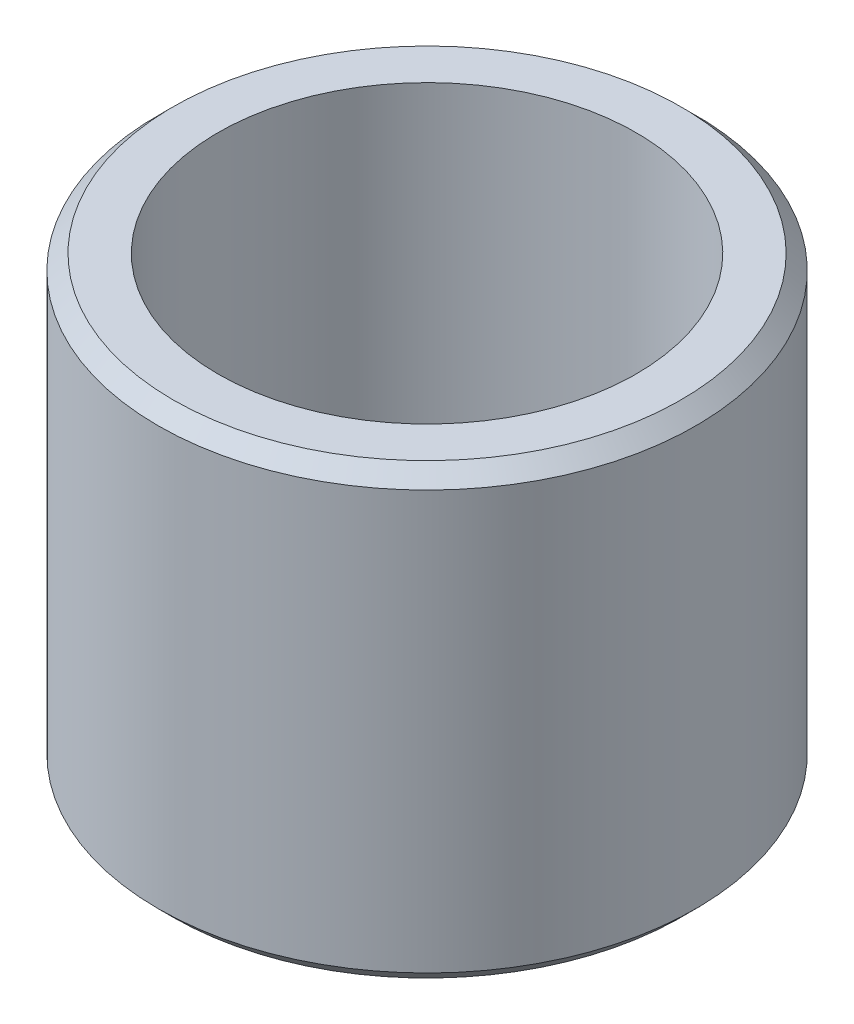
SolidWorks part; units mm, degrees
ref_plane "Front Plane" through (0, 0, 0) normal (0, 0, 1) x (1, 0, 0)
ref_plane "Top Plane" through (0, 0, 0) normal (0, 1, 0) x (1, 0, 0)
ref_plane "Right Plane" through (0, 0, 0) normal (1, 0, 0) x (0, 0, -1)
sketch "Sketch1" plane through (0, 0, 0) normal (0, 1, 0) x (1, 0, 0)
  circle A0 centre (0, 0) radius 9
  circle A1 centre (0, 0) radius 7
extrude "Boss-Extrude1" add sketch "Sketch1" along normal blind 15
chamfer "Chamfer1" distance 0.5 angle 45 2 edges at (0, 0, 9) (0, 15, 9)
